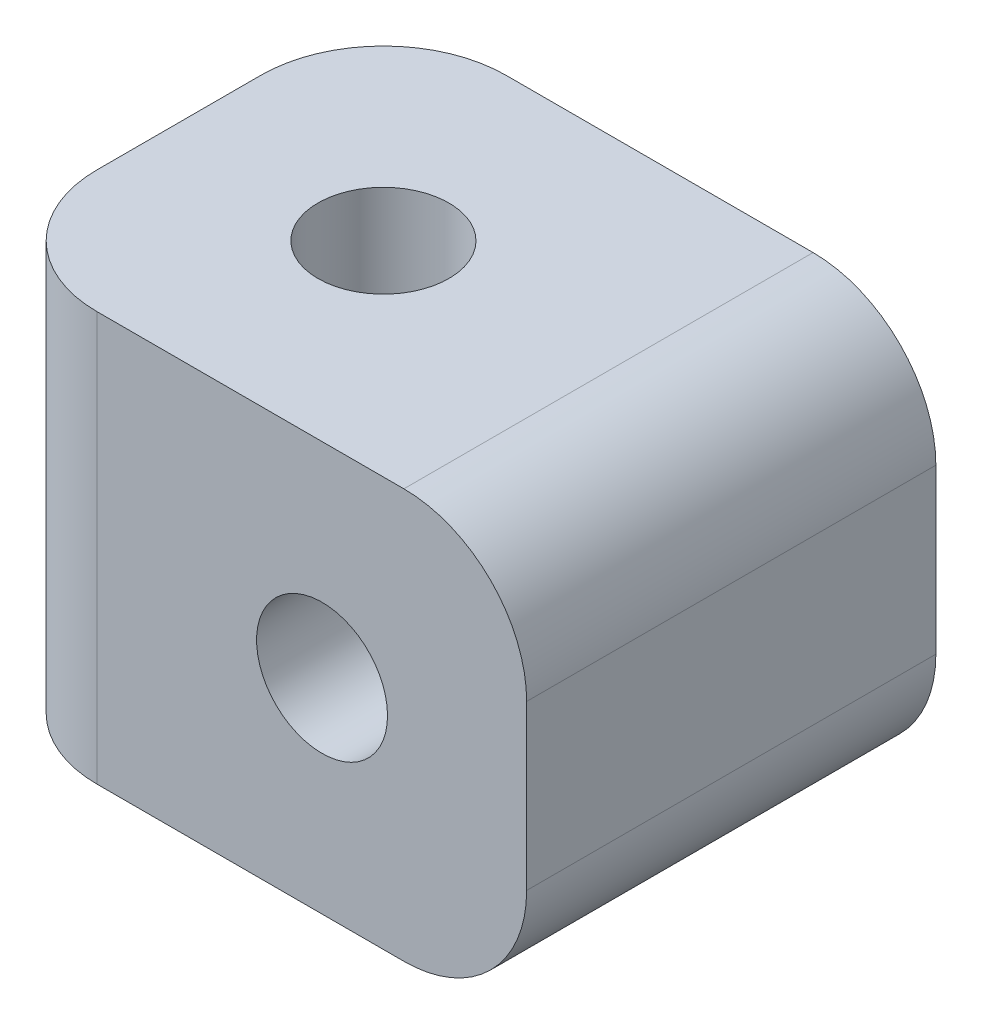
SolidWorks part; units mm, degrees
ref_plane "Front" through (0, 0, 0) normal (0, 0, 1) x (1, 0, 0)
ref_plane "Top" through (0, 0, 0) normal (0, 1, 0) x (1, 0, 0)
ref_plane "Right" through (0, 0, 0) normal (1, 0, 0) x (0, 0, -1)
sketch "Sketch1" plane through (0, 0, 0) normal (0, 1, 0) x (1, 0, 0)
  line L1 (0, 0) -> (13.5, 0)
  line L2 (0, 0) -> (0, -10)
  line L3 (0, -10) -> (13.5, -10)
  line L4 (13.5, 0) -> (13.5, -10)
  dimension "D1" = 13.5
  dimension "D2" = 10
extrude "Boss-Extrude1" add sketch "Sketch1" along normal blind 10
sketch "Sketch2" plane through (0, 0, 10) normal (0, 0, 1) x (1, 0, 0)
  line L0 (0, 0) -> (13.5, 0) construction
  line L1 (13.5, 10) -> (13.5, 0) construction
  circle A0 centre (8.5, 5) radius 1.6
  dimension "D1" = 3.2
  dimension "D2" = 5
  dimension "D3" = 5
extrude "Cut-Extrude1" cut sketch "Sketch2" against normal through all
sketch "Sketch3" plane through (0, 10, 0) normal (0, 1, 0) x (1, 0, 0)
  line L0 (0, -10) -> (13.5, -10) construction
  line L1 (0, 0) -> (0, -10) construction
  circle A0 centre (5, -5) radius 1.6
  dimension "D1" = 3.2
  dimension "D2" = 5
  dimension "D3" = 5
extrude "Cut-Extrude2" cut sketch "Sketch3" against normal through all
fillet "Fillet1" radius 3 4 edges at (13.5, 10, 5) (13.5, 0, 5) (0, 5, 0) (0, 5, 10)
